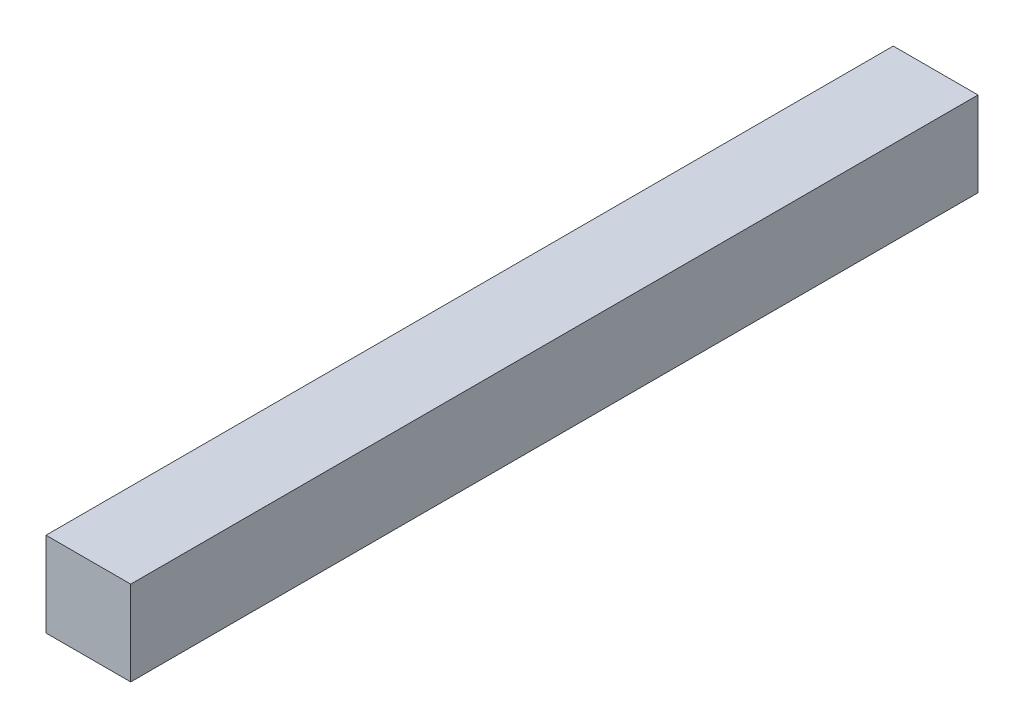
SolidWorks part; units mm, degrees
ref_plane "前视基准面" through (0, 0, 0) normal (0, 0, 1) x (1, 0, 0)
ref_plane "上视基准面" through (0, 0, 0) normal (0, 1, 0) x (1, 0, 0)
ref_plane "右视基准面" through (0, 0, 0) normal (1, 0, 0) x (0, 0, -1)
sketch "草图1" plane through (0, 0, 0) normal (0, 0, 1) x (1, 0, 0)
  line L1 (0, 0) -> (20, 0)
  line L2 (0, 0) -> (0, 20)
  line L3 (0, 20) -> (20, 20)
  line L4 (20, 0) -> (20, 20)
  dimension "D1" = 20
  dimension "D2" = 20
extrude "凸台-拉伸1" add sketch "草图1" along normal blind 200
